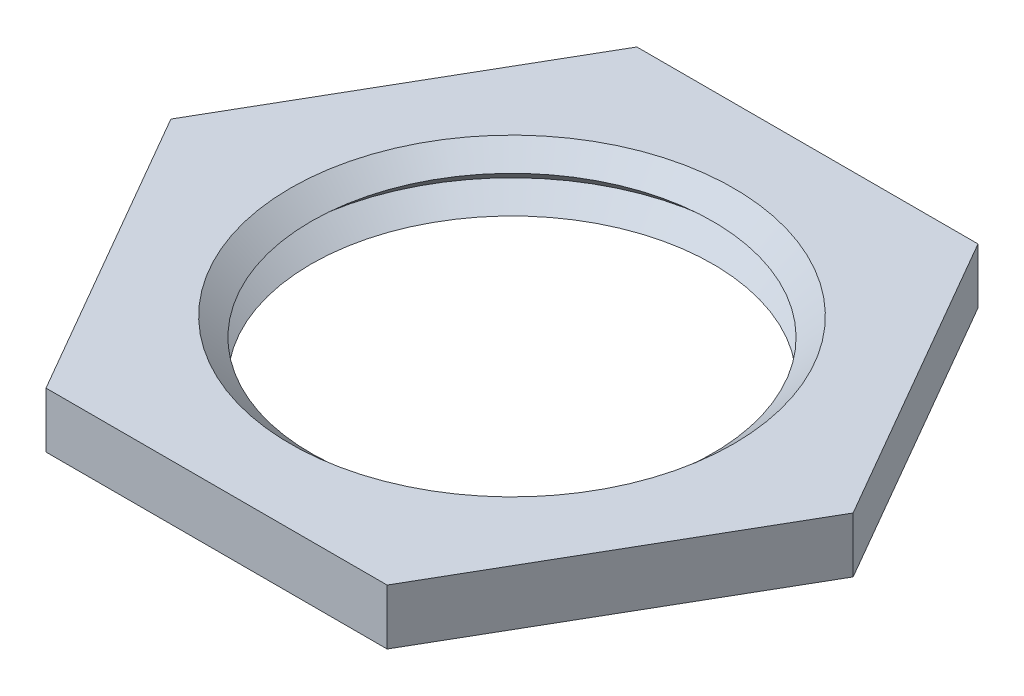
SolidWorks part; units mm, degrees
material "Plain Carbon Steel"
ref_plane "Front Plane" through (0, 0, 0) normal (0, 0, 1) x (1, 0, 0)
ref_plane "Top Plane" through (0, 0, 0) normal (0, 1, 0) x (1, 0, 0)
ref_plane "Right Plane" through (0, 0, 0) normal (1, 0, 0) x (0, 0, -1)
sketch "Sketch1" plane through (0, 0, 0) normal (0, 1, 0) x (1, 0, 0)
  line L1 (7.3323, 0) -> (3.6662, 6.35)
  line L2 (3.6662, 6.35) -> (-3.6662, 6.35)
  line L3 (-3.6662, 6.35) -> (-7.3323, 0)
  line L4 (-7.3323, 0) -> (-3.6662, -6.35)
  line L5 (-3.6662, -6.35) -> (3.6662, -6.35)
  line L6 (3.6662, -6.35) -> (7.3323, 0)
  circle A0 centre (0, 0) radius 6.35 construction
  circle A1 centre (0, 0) radius 4.318
  dimension "D2" = 8.636
  dimension "D1" = 12.7
extrude "Boss-Extrude1" add sketch "Sketch1" along normal blind 1.191
sketch "Sketch2" plane through (0, 0, 0) normal (0, 0, 1) x (1, 0, 0)
  line L0 (4.7625, 1.191) -> (4.318, 0.794)
  line L1 (4.318, 0.794) -> (4.7625, 0.397)
  line L3 (4.7625, 0.397) -> (4.318, 0)
  line L4 (3.6662, 1.191) -> (7.3323, 1.191) construction
  line L5 (4.7625, 1.191) -> (0, 1.191)
  line L6 (4.318, 0) -> (4.318, 1.191) construction
  line L7 (-3.6662, 1.191) -> (3.6662, 1.191) construction
  line L8 (0, 1.191) -> (0, 0)
  line L9 (0, 0) -> (4.318, 0)
  dimension "D1" = 0.397
  dimension "D2" = 0.397
  dimension "D3" = 4.7625
  dimension "D4" = 4.7625
revolve "Cut-Revolve1" cut sketch "Sketch2" angle 360 about L8
equation "\"D2@Sketch2\"=\"D1@Sketch2\""
equation "\"D4@Sketch2\"=\"D3@Sketch2\""
